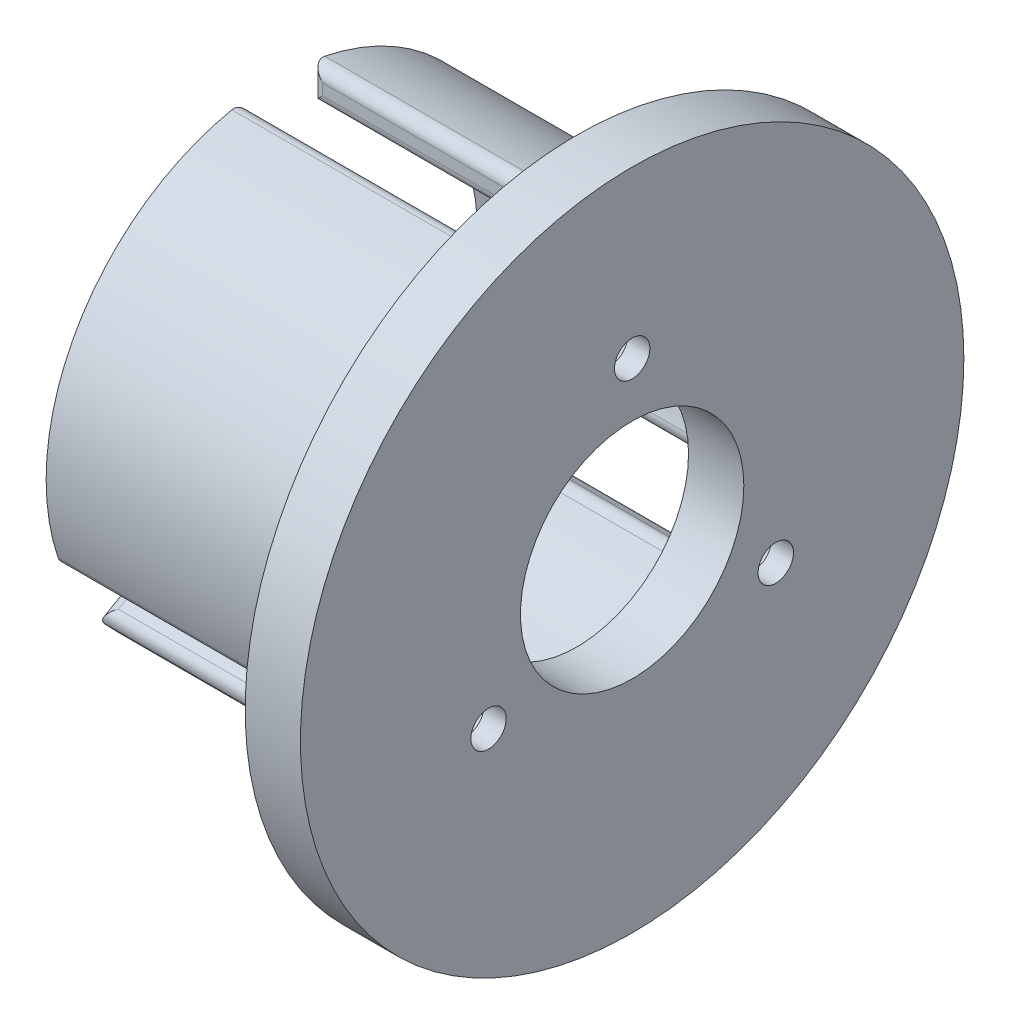
SolidWorks part; units mm, degrees
ref_plane "前视基准面" through (0, 0, 0) normal (0, 0, 1) x (1, 0, 0)
ref_plane "上视基准面" through (0, 0, 0) normal (0, 1, 0) x (1, 0, 0)
ref_plane "右视基准面" through (0, 0, 0) normal (1, 0, 0) x (0, 0, -1)
other "Configuration Table"
sketch "草图1" plane through (0, 0, 0) normal (1, 0, 0) x (0, 0, -1)
  circle A0 centre (0, 0) radius 30
  circle A1 centre (0, 0) radius 10.1
  dimension "D1" = 60
  dimension "D2" = 20.2
extrude "凸台-拉伸1" add sketch "草图1" along normal blind 5
sketch "草图2" plane through (0, 0, 0) normal (-1, 0, 0) x (0, 0, 1)
  line L0 (-3, 20.7846) -> (-3, 17.7482)
  line L1 (-3, 25) -> (3, 25) construction
  line L2 (-3, 0) -> (3, 0) construction
  line L3 (3, 20.7846) -> (3, 17.7482)
  line L4 (-2.0167, 20.9029) -> (-1.3086, 17.9524) construction
  line L5 (-3, 0) -> (-2.5174, 2.0107) construction
  line L6 (19.5, -7.7942) -> (16.8704, -6.276)
  line L7 (16.5, -12.9904) -> (13.8704, -11.4722)
  line L8 (-16.5, -12.9904) -> (-13.8704, -11.4722)
  line L9 (-19.5, -7.7942) -> (-16.8704, -6.276)
  line L10 (-23.0639, -9.8518) -> (-19.5, -7.7942) construction
  line L11 (-16.8704, -6.276) -> (-3, 1.7321) construction
  line L12 (-2.5174, 2.0107) -> (-0.7036, 3.0579) construction
  line L13 (-13.8704, -11.4722) -> (0, -3.4641) construction
  line L14 (0, -3.4641) -> (2.5, -2.0207) construction
  line L15 (-20.0639, -15.048) -> (-16.5, -12.9904) construction
  line L16 (20.0639, -15.048) -> (16.5, -12.9904) construction
  line L17 (23.0639, -9.8518) -> (19.5, -7.7942) construction
  line L18 (16.8704, -6.276) -> (3, 1.7321) construction
  line L19 (3, 1.7321) -> (2.5174, 2.0107) construction
  line L20 (13.8704, -11.4722) -> (0, -3.4641) construction
  line L21 (0, -3.4641) -> (-2.5, -2.0207) construction
  line L22 (3, 25) -> (3, 20.7846) construction
  line L23 (2.0167, 20.9029) -> (3, 25) construction
  line L24 (-3, 25) -> (-2.0167, 20.9029) construction
  line L25 (-3, 25) -> (-3, 20.7846) construction
  line L26 (-1.3086, 17.9524) -> (0, 12.5) construction
  line L27 (2.5174, 2.0107) -> (3, 0) construction
  line L28 (-3, 17.7482) -> (-3, 1.7321) construction
  line L29 (-3, 1.7321) -> (-3, 0) construction
  line L30 (0, 12.5) -> (1.3086, 17.9524) construction
  line L31 (1.3086, 17.9524) -> (2.0167, 20.9029) construction
  line L32 (3, 17.7482) -> (3, 1.7321) construction
  line L33 (3, 1.7321) -> (3, 0) construction
  line L34 (0, 12.5) -> (2.5174, 2.0107) construction
  line L35 (2.5174, 2.0107) -> (0.7036, 3.0579) construction
  line L36 (-2.5174, 2.0107) -> (0, 12.5) construction
  line L37 (-3, 1.7321) -> (-2.5174, 2.0107) construction
  arc A0 (-13.8704, -11.4722) -> (13.8704, -11.4722) centre (0, 0) ccw
  arc A1 (-16.5, -12.9904) -> (16.5, -12.9904) centre (0, 0) ccw
  arc A2 (-19.5, -7.7942) -> (-16.5, -12.9904) centre (0, 0) ccw construction
  circle A3 centre (0, 0) radius 21 construction
  arc A4 (-16.8704, -6.276) -> (-13.8704, -11.4722) centre (0, 0) ccw construction
  circle A5 centre (0, 0) radius 18 construction
  arc A6 (16.5, -12.9904) -> (19.5, -7.7942) centre (0, 0) ccw construction
  arc A7 (19.5, -7.7942) -> (3, 20.7846) centre (0, 0) ccw
  arc A8 (13.8704, -11.4722) -> (16.8704, -6.276) centre (0, 0) ccw construction
  arc A9 (16.8704, -6.276) -> (3, 17.7482) centre (0, 0) ccw
  arc A10 (2.0167, 20.9029) -> (-2.0167, 20.9029) centre (0, 0) ccw construction
  arc A11 (-3, 20.7846) -> (-19.5, -7.7942) centre (0, 0) ccw
  arc A12 (1.3086, 17.9524) -> (-1.3086, 17.9524) centre (0, 0) ccw construction
  arc A13 (-3, 17.7482) -> (-16.8704, -6.276) centre (0, 0) ccw
  arc A14 (-2.0167, 20.9029) -> (-3, 20.7846) centre (0, 0) ccw construction
  arc A15 (-1.3086, 17.9524) -> (-3, 17.7482) centre (0, 0) ccw construction
  arc A16 (3, 17.7482) -> (1.3086, 17.9524) centre (0, 0) ccw construction
  arc A17 (3, 20.7846) -> (2.0167, 20.9029) centre (0, 0) ccw construction
  point P6 (0, 12.5)
  point P20 (0, 0)
  dimension "D1" = 36
  dimension "D3" = 6
  dimension "D4" = 25
  dimension "D2" = 3
  dimension "D5" = 3
extrude "凸台-拉伸2" add sketch "草图2" along normal blind 27
sketch "草图3" plane through (0, 0, 0) normal (-1, 0, 0) x (0, 0, 1)
  circle A0 centre (0, 15) radius 3.1
  circle A1 centre (12.9904, -7.5) radius 3.1
  circle A2 centre (-12.9904, -7.5) radius 3.1
  point P10 (0, 0)
  dimension "D1" = 6.2
  dimension "D2" = 15
  dimension "D3" = 3
extrude "切除-拉伸1" cut sketch "草图3" against normal blind 3
sketch "草图4" plane through (3, 0, 0) normal (-1, 0, 0) x (0, 0, 1)
  circle A0 centre (0, 15) radius 1.6
  circle A1 centre (12.9904, -7.5) radius 1.6
  circle A2 centre (-12.9904, -7.5) radius 1.6
  point P9 (0, 0)
  dimension "D2" = 3.2
  dimension "D1" = 15
  dimension "D3" = 3
extrude "切除-拉伸2" cut sketch "草图4" against normal through all
fillet "圆角1" radius 1 30 edges at (0, 10.5, 18.1865) (0, 9, 15.5885) (0, -18, 0) (0, -21, 0) (0, 10.5, -18.1865) (0, 9, -15.5885) (-13.5, -6.276, 16.8704) (-27, -7.0351, 18.1852) (-13.5, -7.7942, 19.5) (0, -7.0351, 18.1852) (-13.5, 20.7846, 3) (-27, 19.2664, 3) (-13.5, 17.7482, 3) (0, 19.2664, 3) (-13.5, -12.9904, 16.5) (-27, -12.2313, 15.1852) (-13.5, -11.4722, 13.8704) (0, -12.2313, 15.1852) (-13.5, -11.4722, -13.8704) (-27, -12.2313, -15.1852) (-13.5, -12.9904, -16.5) (0, -12.2313, -15.1852) (-13.5, 17.7482, -3) (-27, 19.2664, -3) (-13.5, 20.7846, -3) (0, 19.2664, -3) (-13.5, -7.7942, -19.5) (-27, -7.0351, -18.1852) (-13.5, -6.276, -16.8704) (0, -7.0351, -18.1852)
